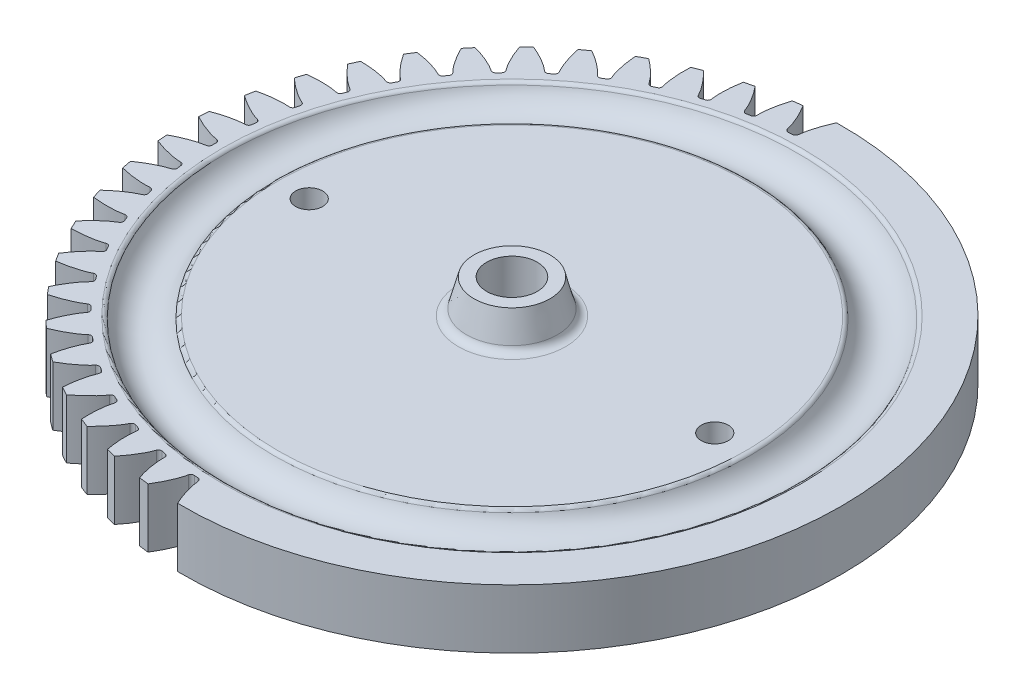
SolidWorks part; units mm, degrees
ref_plane "前视基准面" through (0, 0, 0) normal (0, 0, 1) x (1, 0, 0)
ref_plane "上视基准面" through (0, 0, 0) normal (0, 1, 0) x (1, 0, 0)
ref_plane "右视基准面" through (0, 0, 0) normal (1, 0, 0) x (0, 0, -1)
ref_plane "基准面1" through (0, 0, 0) normal (0, 0, -1) x (-1, 0, 0)
sketch "草图1" plane through (0, 0, 0) normal (0, 0, -1) x (-1, 0, 0)
  line L0 (-39, -7) -> (0, -7)
  line L1 (0, -7) -> (0, 0)
  line L2 (0, 0) -> (-28.0129, 0)
  line L3 (-33.9871, 0) -> (-39, 0)
  line L4 (-39, 0) -> (-39, -7)
  line L5 (0, -7) -> (0, 0) construction
  arc A0 (-28.0129, 0) -> (-33.9871, 0) centre (-31, 1) cw
  dimension "D1" = 3.15
  dimension "D2" = 5.0129
  dimension "D3" = 8
  dimension "D4" = 7
  dimension "D5" = 39
revolve "旋转1" add sketch "草图1" angle 360 about L5
sketch "草图2" plane through (0, -7, 0) normal (0, -1, 0) x (1, 0, 0)
  arc A0 (-1.6317, -35.2007) -> (-2.793, -35.1276) centre (0, 0) cw
  arc A1 (-4.3126, -38.7608) -> (-0.5795, -38.9957) centre (0, 0) ccw
  circle A2 centre (0, 0) radius 39 construction
  ellipse E0 centre (0.3268, -38.0783) end of major axis (1.9435, -41.9121) minor radius 1.2 (-1.6317, -35.2007) -> (-0.5795, -38.9957) ccw
  ellipse E1 centre (-5.0967, -37.737) end of major axis (-7.1811, -41.338) minor radius 1.2 (-4.3126, -38.7608) -> (-2.793, -35.1276) ccw
  point P0 (0.3268, -38.0783)
  point P1 (1.4326, -37.612)
  point P2 (1.9435, -41.9121)
  point P3 (-1.6317, -35.2007)
  point P4 (-0.5795, -38.9957)
  point P5 (-1.3943, -36.7453)
  point P6 (2.048, -39.4112)
  point P16 (-5.0967, -37.737)
  point P17 (-4.0582, -38.3382)
  point P18 (-3.0124, -34.136)
  point P19 (-4.3126, -38.7608)
  point P20 (-2.793, -35.1276)
  point P21 (-3.2221, -36.6303)
  point P22 (-6.9713, -38.8438)
  dimension "D1" = 35.2385
  dimension "D2" = 39
  dimension "D3" = 0.3268
  dimension "D4" = 1.4326
  dimension "D5" = 1.9435
  dimension "D6" = 2.048
  dimension "D7" = 0.5795
  dimension "D8" = 1.6317
  dimension "D9" = 2.793
  dimension "D10" = 1.3943
  dimension "D11" = 3.0124
  dimension "D12" = 4.0582
  dimension "D13" = 4.3126
  dimension "D14" = 3.2221
  dimension "D15" = 5.0967
  dimension "D16" = 34.136
  dimension "D17" = 34.2444
  dimension "D19" = 6.9713
  dimension "D21" = 36.6303
  dimension "D22" = 36.7453
  dimension "D30" = 38.8438
  dimension "D32" = 39.4112
extrude "切除-拉伸1" cut sketch "草图2" against normal through all
sketch "草图3" plane through (0, -7, 0) normal (0, -1, 0) x (1, 0, 0)
  arc A0 (-6.0306, -34.7186) -> (-7.1736, -34.5006) centre (0, 0) cw
  arc A1 (-9.1366, -37.9147) -> (-5.4623, -38.6156) centre (0, 0) ccw
  ellipse E0 centre (-4.4482, -37.819) end of major axis (-3.3248, -41.8252) minor radius 1.2 (-6.0306, -34.7186) -> (-5.4623, -38.6156) ccw
  ellipse E1 centre (-9.7863, -36.8007) end of major axis (-12.3055, -40.112) minor radius 1.2 (-9.1366, -37.9147) -> (-7.1736, -34.5006) ccw
  point P0 (-4.4482, -37.819)
  point P1 (-3.2927, -37.495)
  point P2 (-3.3248, -41.8252)
  point P3 (-6.0306, -34.7186)
  point P4 (-5.4623, -38.6156)
  point P5 (-5.9887, -36.2808)
  point P6 (-2.9077, -39.3571)
  point P16 (-9.7863, -36.8007)
  point P17 (-8.8312, -37.5273)
  point P18 (-7.267, -33.4893)
  point P19 (-9.1366, -37.9147)
  point P20 (-7.1736, -34.5006)
  point P21 (-7.7877, -35.9376)
  point P22 (-11.7848, -37.6637)
  dimension "D1" = 35.2385
  dimension "D2" = 39
  dimension "D3" = 0.5795
  dimension "D4" = 2.3283
  dimension "D5" = 2.7133
  dimension "D6" = 2.7454
  dimension "D7" = 3.8687
  dimension "D8" = 4.8829
  dimension "D9" = 5.4512
  dimension "D10" = 6.5942
  dimension "D11" = 5.4092
  dimension "D12" = 6.6875
  dimension "D13" = 8.2517
  dimension "D14" = 8.5571
  dimension "D15" = 7.2083
  dimension "D16" = 9.2068
  dimension "D17" = 0.3801
  dimension "D20" = 11.2053
  dimension "D22" = 1.332
  dimension "D26" = 2.7149
  dimension "D28" = 3.0581
  dimension "D34" = 0.3614
extrude "切除-拉伸2" cut sketch "草图3" against normal through all
sketch "草图4" plane through (0, -7, 0) normal (0, -1, 0) x (1, 0, 0)
  arc A0 (-10.3345, -33.689) -> (-11.4411, -33.3294) centre (0, 0) cw
  arc A1 (-13.8165, -36.4706) -> (-10.2591, -37.6265) centre (0, 0) ccw
  ellipse E0 centre (-9.1531, -36.9632) end of major axis (-8.5407, -41.0787) minor radius 1.2 (-10.3345, -33.689) -> (-10.2591, -37.6265) ccw
  ellipse E1 centre (-14.3214, -35.2839) end of major axis (-11.407, -32.3144) minor radius 1.2 (-13.8165, -36.4706) -> (-11.4411, -33.3294) ccw
  point P0 (-9.1531, -36.9632)
  point P1 (-7.9661, -36.7866)
  point P2 (-8.5407, -41.0787)
  point P3 (-10.3345, -33.689)
  point P4 (-10.2591, -37.6265)
  point P5 (-10.4886, -35.2441)
  point P6 (-7.8175, -38.6823)
  point P16 (-14.3214, -35.2839)
  point P17 (-13.465, -36.1245)
  point P18 (-11.407, -32.3144)
  point P19 (-13.8165, -36.4706)
  point P20 (-11.4411, -33.3294)
  point P21 (-12.2305, -34.6782)
  point P22 (-16.4124, -35.8897)
  dimension "D1" = 35.2385
  dimension "D2" = 39
  dimension "D3" = 1.6317
  dimension "D4" = 6.1859
  dimension "D5" = 6.3345
  dimension "D6" = 6.909
  dimension "D7" = 7.5214
  dimension "D8" = 8.6274
  dimension "D9" = 8.7028
  dimension "D10" = 9.7753
  dimension "D11" = 9.8095
  dimension "D12" = 8.857
  dimension "D13" = 11.8333
  dimension "D14" = 12.1848
  dimension "D15" = 10.5988
  dimension "D16" = 12.6898
  dimension "D17" = 0.0785
  dimension "D18" = 0.5074
  dimension "D20" = 14.7807
  dimension "D26" = 2.8711
  dimension "D28" = 3.5167
  dimension "D29" = 4.0826
extrude "切除-拉伸3" cut sketch "草图4" against normal through all
sketch "草图5" plane through (0, -7, 0) normal (0, -1, 0) x (1, 0, 0)
  arc A0 (-14.4753, -32.1281) -> (-15.5282, -31.6327) centre (0, 0) cw
  arc A1 (-18.2785, -34.4513) -> (-14.894, -36.044) centre (0, 0) ccw
  ellipse E0 centre (-13.7136, -35.5246) end of major axis (-13.6219, -39.6843) minor radius 1.2 (-14.4753, -32.1281) -> (-14.894, -36.044) ccw
  ellipse E1 centre (-18.6308, -33.2108) end of major axis (-21.8944, -35.7916) minor radius 1.2 (-18.2785, -34.4513) -> (-15.5282, -31.6327) ccw
  point P0 (-13.7136, -35.5246)
  point P1 (-12.5139, -35.4981)
  point P2 (-13.6219, -39.6843)
  point P3 (-14.4753, -32.1281)
  point P4 (-14.894, -36.044)
  point P5 (-14.8232, -33.6517)
  point P6 (-12.6041, -37.3975)
  point P16 (-18.6308, -33.2108)
  point P17 (-15.3671, -30.63)
  point P18 (-19.3751, -32.2695)
  point P19 (-18.2785, -34.4513)
  point P20 (-15.5282, -31.6327)
  point P21 (-16.4804, -32.8719)
  point P22 (-20.7811, -33.5497)
  dimension "D1" = 35.2385
  dimension "D2" = 39
  dimension "D3" = 4.3126
  dimension "D4" = 8.2013
  dimension "D5" = 8.2915
  dimension "D6" = 9.3093
  dimension "D7" = 9.4011
  dimension "D8" = 10.1628
  dimension "D9" = 10.5815
  dimension "D10" = 10.5106
  dimension "D11" = 11.0546
  dimension "D12" = 11.2156
  dimension "D13" = 13.5738
  dimension "D14" = 13.966
  dimension "D15" = 12.1678
  dimension "D16" = 14.3182
  dimension "D17" = 1.3633
  dimension "D18" = 2.7169
  dimension "D20" = 16.4686
  dimension "D26" = 5.1092
  dimension "D27" = 5.2111
  dimension "D29" = 5.889
extrude "切除-拉伸4" cut sketch "草图5" against normal through all
sketch "草图6" plane through (0, -7, 0) normal (0, -1, 0) x (1, 0, 0)
  arc A0 (-18.3879, -30.0605) -> (-19.3704, -29.437) centre (0, 0) cw
  arc A1 (-22.4523, -31.8888) -> (-19.2941, -33.893) centre (0, 0) ccw
  ellipse E0 centre (-18.0579, -33.5257) end of major axis (-18.4882, -37.6641) minor radius 1.2 (-18.3879, -30.0605) -> (-19.2941, -33.893) ccw
  ellipse E1 centre (-22.6463, -30.6138) end of major axis (-19.0849, -28.4624) minor radius 1.2 (-22.4523, -31.8888) -> (-19.3704, -29.437) ccw
  point P0 (-18.0579, -33.5257)
  point P1 (-16.8643, -33.6498)
  point P2 (-18.4882, -37.6641)
  point P3 (-18.3879, -30.0605)
  point P4 (-19.2941, -33.893)
  point P5 (-18.924, -31.5285)
  point P6 (-17.1918, -35.5229)
  point P16 (-22.6463, -30.6138)
  point P17 (-19.0849, -28.4624)
  point P18 (-23.2668, -29.5867)
  point P19 (-22.4523, -31.8888)
  point P20 (-19.3704, -29.437)
  point P21 (-20.4704, -30.5471)
  point P22 (-24.8222, -30.6806)
  dimension "D1" = 35.2385
  dimension "D2" = 39
  dimension "D3" = 6.0306
  dimension "D4" = 10.8337
  dimension "D5" = 11.1612
  dimension "D6" = 11.597
  dimension "D7" = 12.0273
  dimension "D8" = 12.3573
  dimension "D9" = 13.0543
  dimension "D10" = 12.8934
  dimension "D11" = 13.2635
  dimension "D12" = 13.3398
  dimension "D13" = 15.9951
  dimension "D14" = 16.4217
  dimension "D15" = 14.4397
  dimension "D16" = 16.6156
  dimension "D17" = 0.6075
  dimension "D20" = 18.7915
  dimension "D25" = 2.9721
  dimension "D26" = 3.82
  dimension "D28" = 3.9535
  dimension "D35" = 1.0223
extrude "切除-拉伸5" cut sketch "草图6" against normal through all
sketch "草图7" plane through (0, -7, 0) normal (0, -1, 0) x (1, 0, 0)
  arc A0 (-22.0105, -27.5189) -> (-22.9071, -26.7771) centre (0, 0) cw
  arc A1 (-26.272, -28.8233) -> (-23.3899, -31.2076) centre (0, 0) ccw
  ellipse E0 centre (-22.1174, -30.9981) end of major axis (-21.1718, -26.9462) minor radius 1.2 (-22.0105, -27.5189) -> (-23.3899, -31.2076) ccw
  ellipse E1 centre (-26.3046, -27.5341) end of major axis (-30.1075, -29.2222) minor radius 1.2 (-26.272, -28.8233) -> (-22.9071, -26.7771) ccw
  point P0 (-22.1174, -30.9981)
  point P1 (-20.9488, -31.2708)
  point P2 (-23.063, -35.0499)
  point P3 (-22.0105, -27.5189)
  point P4 (-23.3899, -31.2076)
  point P5 (-22.7263, -28.908)
  point P6 (-21.5085, -33.0881)
  point P16 (-26.3046, -27.5341)
  point P17 (-22.5017, -25.846)
  point P18 (-26.7915, -26.4373)
  point P19 (-26.272, -28.8233)
  point P20 (-22.9071, -26.7771)
  point P21 (-24.1375, -27.7406)
  point P22 (-28.4717, -27.3276)
  dimension "D1" = 35.2385
  dimension "D2" = 39
  dimension "D3" = 9.1366
  dimension "D4" = 11.8122
  dimension "D5" = 12.0352
  dimension "D6" = 12.3719
  dimension "D7" = 12.8739
  dimension "D8" = 12.9808
  dimension "D9" = 13.3651
  dimension "D10" = 13.5898
  dimension "D11" = 13.7705
  dimension "D12" = 14.2533
  dimension "D13" = 16.6812
  dimension "D14" = 17.1354
  dimension "D15" = 15.0009
  dimension "D16" = 17.168
  dimension "D17" = 2.8647
  dimension "D18" = 4.8266
  dimension "D20" = 19.3351
  dimension "D25" = 9.0066
  dimension "D28" = 10.1741
  dimension "D31" = 10.5871
extrude "切除-拉伸6" cut sketch "草图7" against normal through all
sketch "草图8" plane through (0, -7, 0) normal (0, -1, 0) x (1, 0, 0)
  arc A0 (-25.286, -24.5432) -> (-26.0825, -23.695) centre (0, 0) cw
  arc A1 (-29.6773, -25.3033) -> (-27.1168, -28.03) centre (0, 0) ccw
  ellipse E0 centre (-25.8281, -27.9816) end of major axis (-27.2741, -31.883) minor radius 1.2 (-25.286, -24.5432) -> (-27.1168, -28.03) ccw
  ellipse E1 centre (-29.5481, -24.0202) end of major axis (-25.5636, -22.822) minor radius 1.2 (-29.6773, -25.3033) -> (-26.0825, -23.695) ccw
  point P0 (-25.8281, -27.9816)
  point P1 (-24.7029, -28.3986)
  point P2 (-27.2741, -31.883)
  point P3 (-25.286, -24.5432)
  point P4 (-27.1168, -28.03)
  point P5 (-26.1703, -25.8317)
  point P6 (-25.4859, -30.1315)
  point P16 (-29.5481, -24.0202)
  point P17 (-25.5636, -22.822)
  point P18 (-29.8937, -22.871)
  point P19 (-29.6773, -25.3033)
  point P20 (-26.0825, -23.695)
  point P21 (-27.424, -24.4966)
  point P22 (-31.6723, -23.5437)
  dimension "D1" = 35.2385
  dimension "D2" = 39
  dimension "D3" = 10.3345
  dimension "D4" = 14.0477
  dimension "D5" = 14.3684
  dimension "D6" = 14.9515
  dimension "D7" = 15.1515
  dimension "D8" = 15.2292
  dimension "D9" = 15.4936
  dimension "D10" = 15.7481
  dimension "D11" = 15.8358
  dimension "D12" = 16.7823
  dimension "D13" = 18.8681
  dimension "D14" = 19.2137
  dimension "D15" = 17.0895
  dimension "D16" = 19.3429
  dimension "D17" = 1.4464
  dimension "D18" = 3.198
  dimension "D20" = 21.3378
  dimension "D24" = 7.4977
  dimension "D29" = 8.8328
  dimension "D33" = 9.7858
extrude "切除-拉伸7" cut sketch "草图8" against normal through all
sketch "草图9" plane through (0, -7, 0) normal (0, -1, 0) x (1, 0, 0)
  arc A0 (-28.1627, -21.1805) -> (-28.8466, -20.2391) centre (0, 0) cw
  arc A1 (-32.6147, -21.3842) -> (-30.4161, -24.4103) centre (0, 0) ccw
  ellipse E0 centre (-29.1315, -24.5238) end of major axis (-27.2079, -20.8344) minor radius 1.2 (-28.1627, -21.1805) -> (-30.4161, -24.4103) ccw
  ellipse E1 centre (-32.3257, -20.1274) end of major axis (-28.2224, -19.4381) minor radius 1.2 (-32.6147, -21.3842) -> (-28.8466, -20.2391) ccw
  point P0 (-29.1315, -24.5238)
  point P1 (-28.0674, -25.0786)
  point P2 (-31.055, -28.2132)
  point P3 (-28.1627, -21.1805)
  point P4 (-30.4161, -24.4103)
  point P5 (-29.2015, -22.348)
  point P6 (-29.0614, -26.6996)
  point P16 (-32.3257, -20.1274)
  point P17 (-28.2224, -19.4381)
  point P18 (-32.5245, -18.9439)
  point P19 (-32.6147, -21.3842)
  point P20 (-28.8466, -20.2391)
  point P21 (-30.278, -20.8663)
  point P22 (-34.3733, -19.3884)
  dimension "D1" = 35.2385
  dimension "D2" = 39
  dimension "D3" = 13.8165
  dimension "D4" = 13.3914
  dimension "D5" = 14.2509
  dimension "D6" = 14.3462
  dimension "D7" = 14.4059
  dimension "D8" = 15.0301
  dimension "D9" = 15.2449
  dimension "D10" = 15.315
  dimension "D11" = 15.385
  dimension "D12" = 16.5996
  dimension "D13" = 16.4615
  dimension "D14" = 18.3104
  dimension "D15" = 18.5092
  dimension "D16" = 18.7982
  dimension "D17" = 8.2573
  dimension "D18" = 9.771
  dimension "D20" = 20.5568
  dimension "D24" = 14.1226
  dimension "D28" = 15.6043
  dimension "D34" = 17.0822
extrude "切除-拉伸8" cut sketch "草图9" against normal through all
sketch "草图10" plane through (0, -7, 0) normal (0, -1, 0) x (1, 0, 0)
  arc A0 (-30.5952, -17.4838) -> (-31.1558, -16.4641) centre (0, 0) cw
  arc A1 (-35.0376, -17.1279) -> (-33.2356, -20.4057) centre (0, 0) ccw
  ellipse E0 centre (-31.9754, -20.6793) end of major axis (-34.3462, -24.0986) minor radius 1.2 (-30.5952, -17.4838) -> (-33.2356, -20.4057) ccw
  ellipse E1 centre (-34.5934, -15.9172) end of major axis (-30.4361, -15.7476) minor radius 1.2 (-35.0376, -17.1279) -> (-31.1558, -16.4641) ccw
  point P0 (-31.9754, -20.6793)
  point P1 (-30.9892, -21.3631)
  point P2 (-34.3462, -24.0986)
  point P3 (-30.5952, -17.4838)
  point P4 (-33.2356, -20.4057)
  point P5 (-31.7722, -18.5119)
  point P6 (-32.1786, -22.8467)
  point P16 (-34.5934, -15.9172)
  point P17 (-30.4361, -15.7476)
  point P18 (-34.6423, -14.7182)
  point P19 (-35.0376, -17.1279)
  point P20 (-31.1558, -16.4641)
  point P21 (-32.6545, -16.907)
  point P22 (-36.5323, -14.9274)
  dimension "D1" = 35.2385
  dimension "D2" = 39
  dimension "D3" = 14.4753
  dimension "D4" = 15.1293
  dimension "D5" = 15.9608
  dimension "D6" = 16.1199
  dimension "D7" = 16.5139
  dimension "D8" = 16.6805
  dimension "D9" = 17.2968
  dimension "D10" = 17.5001
  dimension "D11" = 17.7033
  dimension "D12" = 18.1792
  dimension "D13" = 18.7603
  dimension "D14" = 20.0692
  dimension "D15" = 20.1181
  dimension "D16" = 20.5623
  dimension "D17" = 7.5341
  dimension "D18" = 8.7859
  dimension "D20" = 22.057
  dimension "D24" = 13.1207
  dimension "D29" = 14.7257
  dimension "D34" = 16.7052
extrude "切除-拉伸9" cut sketch "草图10" against normal through all
sketch "草图11" plane through (0, -7, 0) normal (0, -1, 0) x (1, 0, 0)
  arc A0 (-32.5453, -13.5113) -> (-32.9736, -12.4294) centre (0, 0) cw
  arc A1 (-36.908, -12.6014) -> (-35.5311, -16.0792) centre (0, 0) ccw
  ellipse E0 centre (-34.3151, -16.5087) end of major axis (-37.0957, -19.6038) minor radius 1.2 (-32.5453, -13.5113) -> (-35.5311, -16.0792) ccw
  ellipse E1 centre (-36.3156, -11.456) end of major axis (-32.1698, -11.8088) minor radius 1.2 (-36.908, -12.6014) -> (-32.9736, -12.4294) ccw
  point P0 (-34.3151, -16.5087)
  point P1 (-33.4224, -17.3107)
  point P2 (-37.0957, -19.6038)
  point P3 (-32.5453, -13.5113)
  point P4 (-35.5311, -16.0792)
  point P5 (-33.8418, -14.3838)
  point P6 (-34.7883, -18.6335)
  point P16 (-36.3156, -11.456)
  point P17 (-32.1698, -11.8088)
  point P18 (-36.2138, -10.2603)
  point P19 (-36.908, -12.6014)
  point P20 (-32.9736, -12.4294)
  point P21 (-34.516, -12.6809)
  point P22 (-38.1151, -10.231)
  dimension "D1" = 35.2385
  dimension "D2" = 39
  dimension "D3" = 18.2785
  dimension "D4" = 13.2559
  dimension "D5" = 13.8913
  dimension "D6" = 14.2667
  dimension "D7" = 14.6951
  dimension "D8" = 15.1438
  dimension "D9" = 15.5633
  dimension "D10" = 16.0365
  dimension "D11" = 16.2375
  dimension "D12" = 16.5098
  dimension "D13" = 17.2525
  dimension "D14" = 17.9353
  dimension "D15" = 18.037
  dimension "D16" = 18.6295
  dimension "D17" = 14.8475
  dimension "D18" = 15.8178
  dimension "D20" = 19.8366
  dimension "D24" = 20.0675
  dimension "D27" = 21.7704
  dimension "D35" = 24.2203
extrude "切除-拉伸10" cut sketch "草图11" against normal through all
sketch "草图12" plane through (0, -7, 0) normal (0, -1, 0) x (1, 0, 0)
  arc A0 (-33.982, -9.3258) -> (-34.2714, -8.1987) centre (0, 0) cw
  arc A1 (-38.1964, -7.8763) -> (-37.2662, -11.4992) centre (0, 0) ccw
  ellipse E0 centre (-36.1136, -12.0777) end of major axis (-32.9669, -9.3555) minor radius 1.2 (-33.982, -9.3258) -> (-37.2662, -11.4992) ccw
  ellipse E1 centre (-37.465, -6.8141) end of major axis (-33.3962, -7.6837) minor radius 1.2 (-38.1964, -7.8763) -> (-34.2714, -8.1987) ccw
  point P0 (-36.1136, -12.0777)
  point P1 (-32.9669, -9.3555)
  point P2 (-35.3284, -12.9852)
  point P3 (-33.982, -9.3258)
  point P4 (-37.2662, -11.4992)
  point P5 (-35.3777, -10.0289)
  point P6 (-36.8494, -14.1265)
  point P16 (-37.465, -6.8141)
  point P17 (-33.3962, -7.6837)
  point P18 (-37.2142, -5.6406)
  point P19 (-38.1964, -7.8763)
  point P20 (-34.2714, -8.1987)
  point P21 (-35.8332, -8.255)
  point P22 (-39.0969, -5.3732)
  dimension "D1" = 35.2385
  dimension "D2" = 39
  dimension "D3" = 18.3879
  dimension "D4" = 14.579
  dimension "D5" = 15.0083
  dimension "D6" = 15.5941
  dimension "D7" = 15.8835
  dimension "D8" = 16.9405
  dimension "D9" = 16.9898
  dimension "D10" = 17.4453
  dimension "D11" = 17.7257
  dimension "D12" = 18.4615
  dimension "D13" = 18.8263
  dimension "D14" = 18.8783
  dimension "D15" = 19.0771
  dimension "D16" = 19.8085
  dimension "D17" = 14.6371
  dimension "D18" = 15.3106
  dimension "D19" = 20.709
  dimension "D24" = 19.4081
  dimension "D27" = 21.1821
  dimension "D35" = 24.0638
extrude "切除-拉伸11" cut sketch "草图12" against normal through all
sketch "草图13" plane through (0, -7, 0) normal (0, -1, 0) x (1, 0, 0)
  arc A0 (-34.8829, -4.9932) -> (-35.0288, -3.8387) centre (0, 0) cw
  arc A1 (-38.8824, -3.0269) -> (-38.4136, -6.7379) centre (0, 0) ccw
  ellipse E0 centre (-37.3425, -7.4562) end of major axis (-40.8055, -9.7626) minor radius 1.2 (-34.8829, -4.9932) -> (-38.4136, -6.7379) ccw
  ellipse E1 centre (-38.0236, -2.0647) end of major axis (-34.0959, -3.4375) minor radius 1.2 (-38.8824, -3.0269) -> (-35.0288, -3.8387) ccw
  point P0 (-37.3425, -7.4562)
  point P1 (-33.8795, -5.1498)
  point P2 (-36.6773, -8.455)
  point P3 (-34.8829, -4.9932)
  point P4 (-38.4136, -6.7379)
  point P5 (-36.3557, -5.5158)
  point P6 (-38.3294, -9.3966)
  point P16 (-38.0236, -2.0647)
  point P17 (-34.0959, -3.4375)
  point P18 (-37.6277, -0.9319)
  point P19 (-38.8824, -3.0269)
  point P20 (-35.0288, -3.8387)
  point P21 (-36.5853, -3.6988)
  point P22 (-39.462, -0.4307)
  dimension "D1" = 35.2385
  dimension "D2" = 39
  dimension "D3" = 22.0105
  dimension "D4" = 11.869
  dimension "D5" = 12.0854
  dimension "D6" = 12.8724
  dimension "D7" = 13.0183
  dimension "D8" = 14.3452
  dimension "D9" = 14.5748
  dimension "D10" = 14.6668
  dimension "D11" = 15.332
  dimension "D12" = 15.6172
  dimension "D13" = 16.0131
  dimension "D14" = 16.4031
  dimension "D15" = 16.3189
  dimension "D16" = 16.8719
  dimension "D17" = 22.1262
  dimension "D18" = 22.4922
  dimension "D19" = 17.4515
  dimension "D24" = 26.373
  dimension "D28" = 28.19
  dimension "D35" = 31.458
extrude "切除-拉伸12" cut sketch "草图13" against normal through all
sketch "草图14" plane through (0, -7, 0) normal (0, -1, 0) x (1, 0, 0)
  arc A0 (-35.2337, -0.5818) -> (-35.2337, 0.5818) centre (0, 0) cw
  arc A1 (-38.9551, 1.8702) -> (-38.9551, -1.8702) centre (0, 0) ccw
  ellipse E0 centre (-37.9826, -2.7172) end of major axis (-34.2578, -0.863) minor radius 1.2 (-35.2337, -0.5818) -> (-38.9551, -1.8702) ccw
  ellipse E1 centre (-37.9826, 2.7172) end of major axis (-34.2578, 0.863) minor radius 1.2 (-38.9551, 1.8702) -> (-35.2337, 0.5818) ccw
  point P0 (-37.9826, -2.7172)
  point P1 (-34.2578, -0.863)
  point P2 (-37.4478, -3.7914)
  point P3 (-35.2337, -0.5818)
  point P4 (-38.9551, -1.8702)
  point P5 (-36.7603, -0.9157)
  point P6 (-39.2048, -4.5186)
  point P16 (-37.9826, 2.7172)
  point P17 (-34.2578, 0.863)
  point P18 (-37.4478, 3.7914)
  point P19 (-38.9551, 1.8702)
  point P20 (-35.2337, 0.5818)
  point P21 (-36.7603, 0.9157)
  point P22 (-39.2048, 4.5186)
  dimension "D1" = 35.2385
  dimension "D2" = 39
  dimension "D3" = 22.0105
  dimension "D4" = 12.2473
  dimension "D5" = 13.2232
  dimension "D6" = 14.7499
  dimension "D7" = 15.4373
  dimension "D8" = 16.5069
  dimension "D9" = 16.9446
  dimension "D10" = 22.2058
  dimension "D11" = 17.1943
  dimension "D12" = 22.2586
  dimension "D17" = 25.8614
  dimension "D23" = 27.6929
  dimension "D28" = 31.2957
extrude "切除-拉伸13" cut sketch "草图14" against normal through all
sketch "草图15" plane through (0, -7, 0) normal (0, -1, 0) x (1, 0, 0)
  arc A0 (-35.0288, 3.8387) -> (-34.8829, 4.9932) centre (0, 0) cw
  arc A1 (-38.4136, 6.7379) -> (-38.8824, 3.0269) centre (0, 0) ccw
  ellipse E0 centre (-38.0236, 2.0647) end of major axis (-34.0959, 3.4375) minor radius 1.2 (-35.0288, 3.8387) -> (-38.8824, 3.0269) ccw
  ellipse E1 centre (-37.3425, 7.4562) end of major axis (-33.8795, 5.1498) minor radius 1.2 (-38.4136, 6.7379) -> (-34.8829, 4.9932) ccw
  point P0 (-38.0236, 2.0647)
  point P1 (-34.0959, 3.4375)
  point P2 (-37.6277, 0.9319)
  point P3 (-35.0288, 3.8387)
  point P4 (-38.8824, 3.0269)
  point P5 (-36.5853, 3.6988)
  point P6 (-39.462, 0.4307)
  point P16 (-37.3425, 7.4562)
  point P17 (-33.8795, 5.1498)
  point P18 (-36.6773, 8.455)
  point P19 (-38.4136, 6.7379)
  point P20 (-34.8829, 4.9932)
  point P21 (-36.3557, 5.5158)
  point P22 (-38.3294, 9.3966)
  dimension "D1" = 35.2385
  dimension "D2" = 39
  dimension "D3" = 25.286
  dimension "D4" = 8.5936
  dimension "D5" = 8.8099
  dimension "D6" = 9.597
  dimension "D7" = 9.7428
  dimension "D8" = 11.0697
  dimension "D9" = 11.2993
  dimension "D10" = 11.3914
  dimension "D11" = 12.0566
  dimension "D12" = 12.3418
  dimension "D13" = 12.7377
  dimension "D14" = 13.1276
  dimension "D15" = 13.0434
  dimension "D16" = 13.5964
  dimension "D17" = 28.8233
  dimension "D18" = 29.254
  dimension "D19" = 14.1761
  dimension "D26" = 32.5221
  dimension "D30" = 34.3391
  dimension "D35" = 38.2199
extrude "切除-拉伸14" cut sketch "草图15" against normal through all
sketch "草图16" plane through (0, -7, 0) normal (0, -1, 0) x (1, 0, 0)
  arc A0 (-34.2714, 8.1987) -> (-33.982, 9.3258) centre (0, 0) cw
  arc A1 (-37.2662, 11.4992) -> (-38.1964, 7.8763) centre (0, 0) ccw
  ellipse E0 centre (-37.465, 6.8141) end of major axis (-41.5339, 5.9445) minor radius 1.2 (-34.2714, 8.1987) -> (-38.1964, 7.8763) ccw
  ellipse E1 centre (-36.1136, 12.0777) end of major axis (-32.9669, 9.3555) minor radius 1.2 (-37.2662, 11.4992) -> (-33.982, 9.3258) ccw
  point P0 (-37.465, 6.8141)
  point P1 (-33.3962, 7.6837)
  point P2 (-37.2142, 5.6406)
  point P3 (-34.2714, 8.1987)
  point P4 (-38.1964, 7.8763)
  point P5 (-35.8332, 8.255)
  point P6 (-39.0969, 5.3732)
  point P16 (-36.1136, 12.0777)
  point P17 (-32.9669, 9.3555)
  point P18 (-35.3284, 12.9852)
  point P19 (-37.2662, 11.4992)
  point P20 (-33.982, 9.3258)
  point P21 (-35.3777, 10.0289)
  point P22 (-36.8494, 14.1265)
  dimension "D1" = 35.2385
  dimension "D2" = 39
  dimension "D3" = 25.286
  dimension "D4" = 7.681
  dimension "D5" = 8.1102
  dimension "D6" = 8.6961
  dimension "D7" = 8.9855
  dimension "D8" = 10.0425
  dimension "D9" = 10.0918
  dimension "D10" = 10.5472
  dimension "D11" = 10.8276
  dimension "D12" = 11.5635
  dimension "D13" = 11.9283
  dimension "D14" = 11.9802
  dimension "D15" = 12.1791
  dimension "D16" = 12.9104
  dimension "D17" = 23.695
  dimension "D18" = 29.0682
  dimension "D19" = 13.8109
  dimension "D27" = 31.9499
  dimension "D30" = 33.7239
  dimension "D35" = 37.8214
extrude "切除-拉伸15" cut sketch "草图16" against normal through all
sketch "草图17" plane through (0, -7, 0) normal (0, -1, 0) x (1, 0, 0)
  arc A0 (-32.9736, 12.4294) -> (-32.5453, 13.5113) centre (0, 0) cw
  arc A1 (-35.5311, 16.0792) -> (-36.908, 12.6014) centre (0, 0) ccw
  ellipse E0 centre (-36.3156, 11.456) end of major axis (-32.1698, 11.8088) minor radius 1.2 (-32.9736, 12.4294) -> (-36.908, 12.6014) ccw
  ellipse E1 centre (-34.3151, 16.5087) end of major axis (-31.5344, 13.4135) minor radius 1.2 (-35.5311, 16.0792) -> (-32.5453, 13.5113) ccw
  point P0 (-36.3156, 11.456)
  point P1 (-32.1698, 11.8088)
  point P2 (-36.2138, 10.2603)
  point P3 (-32.9736, 12.4294)
  point P4 (-36.908, 12.6014)
  point P5 (-34.516, 12.6809)
  point P6 (-38.1151, 10.231)
  point P16 (-34.3151, 16.5087)
  point P17 (-33.4224, 17.3107)
  point P18 (-37.0957, 19.6038)
  point P19 (-35.5311, 16.0792)
  point P20 (-32.5453, 13.5113)
  point P21 (-33.8418, 14.3838)
  point P22 (-34.7883, 18.6335)
  dimension "D1" = 35.2385
  dimension "D2" = 39
  dimension "D3" = 28.1627
  dimension "D4" = 3.3718
  dimension "D5" = 4.0072
  dimension "D6" = 4.3826
  dimension "D7" = 4.811
  dimension "D8" = 5.2597
  dimension "D9" = 5.6791
  dimension "D10" = 6.1524
  dimension "D11" = 6.3534
  dimension "D12" = 6.6257
  dimension "D13" = 7.3684
  dimension "D14" = 8.0512
  dimension "D15" = 8.1529
  dimension "D16" = 8.7454
  dimension "D17" = 25.3033
  dimension "D18" = 35.5343
  dimension "D20" = 9.9525
  dimension "D27" = 37.9842
  dimension "D30" = 39.6871
  dimension "D35" = 43.9368
extrude "切除-拉伸16" cut sketch "草图17" against normal through all
sketch "草图18" plane through (0, -7, 0) normal (0, -1, 0) x (1, 0, 0)
  arc A0 (-31.1558, 16.4641) -> (-30.5952, 17.4838) centre (0, 0) cw
  arc A1 (-33.2356, 20.4057) -> (-35.0376, 17.1279) centre (0, 0) ccw
  ellipse E0 centre (-34.5934, 15.9172) end of major axis (-30.4361, 15.7476) minor radius 1.2 (-31.1558, 16.4641) -> (-35.0376, 17.1279) ccw
  ellipse E1 centre (-31.9754, 20.6793) end of major axis (-29.6046, 17.2601) minor radius 1.2 (-33.2356, 20.4057) -> (-30.5952, 17.4838) ccw
  point P0 (-34.5934, 15.9172)
  point P1 (-30.4361, 15.7476)
  point P2 (-34.6423, 14.7182)
  point P3 (-31.1558, 16.4641)
  point P4 (-35.0376, 17.1279)
  point P5 (-32.6545, 16.907)
  point P6 (-36.5323, 14.9274)
  point P16 (-31.9754, 20.6793)
  point P17 (-30.9892, 21.3631)
  point P18 (-34.3462, 24.0986)
  point P19 (-33.2356, 20.4057)
  point P20 (-30.5952, 17.4838)
  point P21 (-31.7722, 18.5119)
  point P22 (-32.1786, 22.8467)
  dimension "D1" = 35.2385
  dimension "D2" = 39
  dimension "D3" = 28.1627
  dimension "D4" = 1.442
  dimension "D5" = 2.2735
  dimension "D6" = 2.4326
  dimension "D7" = 2.8266
  dimension "D8" = 2.9931
  dimension "D9" = 3.6095
  dimension "D10" = 3.8127
  dimension "D11" = 4.016
  dimension "D12" = 4.4918
  dimension "D13" = 5.073
  dimension "D14" = 6.3818
  dimension "D15" = 6.4307
  dimension "D16" = 6.875
  dimension "D17" = 20.2391
  dimension "D19" = 35.1666
  dimension "D20" = 8.3696
  dimension "D25" = 37.1461
  dimension "D30" = 38.751
  dimension "D35" = 43.0859
extrude "切除-拉伸17" cut sketch "草图18" against normal through all
sketch "草图19" plane through (0, -7, 0) normal (0, -1, 0) x (1, 0, 0)
  arc A0 (-28.8466, 20.2391) -> (-28.1627, 21.1805) centre (0, 0) cw
  arc A1 (-30.4161, 24.4103) -> (-32.6147, 21.3842) centre (0, 0) ccw
  ellipse E0 centre (-32.3257, 20.1274) end of major axis (-28.2224, 19.4381) minor radius 1.2 (-28.8466, 20.2391) -> (-32.6147, 21.3842) ccw
  ellipse E1 centre (-29.1315, 24.5238) end of major axis (-31.055, 28.2132) minor radius 1.2 (-30.4161, 24.4103) -> (-28.1627, 21.1805) ccw
  point P0 (-32.3257, 20.1274)
  point P1 (-28.2224, 19.4381)
  point P2 (-32.5245, 18.9439)
  point P3 (-28.8466, 20.2391)
  point P4 (-32.6147, 21.3842)
  point P5 (-30.278, 20.8663)
  point P6 (-34.3733, 19.3884)
  point P16 (-29.1315, 24.5238)
  point P17 (-28.0674, 25.0786)
  point P18 (-31.055, 28.2132)
  point P19 (-30.4161, 24.4103)
  point P20 (-28.1627, 21.1805)
  point P21 (-29.2015, 22.348)
  point P22 (-29.0614, 26.6996)
  dimension "D1" = 35.2385
  dimension "D2" = 39
  dimension "D3" = 0.1791
  dimension "D4" = 0.3172
  dimension "D5" = 0.3997
  dimension "D6" = 1.3937
  dimension "D7" = 1.4638
  dimension "D8" = 1.5338
  dimension "D9" = 1.7486
  dimension "D10" = 2.3728
  dimension "D11" = 2.4326
  dimension "D12" = 3.3873
  dimension "D13" = 30.5952
  dimension "D14" = 1.5316
  dimension "D15" = 1.7305
  dimension "D16" = 2.0195
  dimension "D17" = 21.3842
  dimension "D19" = 40.7726
  dimension "D20" = 3.7781
  dimension "D26" = 42.2505
  dimension "D30" = 43.7322
  dimension "D35" = 48.0838
extrude "切除-拉伸18" cut sketch "草图19" against normal through all
sketch "草图20" plane through (0, -7, 0) normal (0, -1, 0) x (1, 0, 0)
  arc A0 (-26.0825, 23.695) -> (-25.286, 24.5432) centre (0, 0) cw
  arc A1 (-27.1168, 28.03) -> (-29.6773, 25.3033) centre (0, 0) ccw
  ellipse E0 centre (-29.5481, 24.0202) end of major axis (-33.5326, 25.2183) minor radius 1.2 (-26.0825, 23.695) -> (-29.6773, 25.3033) ccw
  ellipse E1 centre (-25.8281, 27.9816) end of major axis (-27.2741, 31.883) minor radius 1.2 (-27.1168, 28.03) -> (-25.286, 24.5432) ccw
  point P0 (-29.5481, 24.0202)
  point P1 (-25.5636, 22.822)
  point P2 (-29.8937, 22.871)
  point P3 (-26.0825, 23.695)
  point P4 (-29.6773, 25.3033)
  point P5 (-27.424, 24.4966)
  point P6 (-31.6723, 23.5437)
  point P16 (-25.8281, 27.9816)
  point P17 (-24.7029, 28.3986)
  point P18 (-27.2741, 31.883)
  point P19 (-27.1168, 28.03)
  point P20 (-25.286, 24.5432)
  point P21 (-26.1703, 25.8317)
  point P22 (-25.4859, 30.1315)
  dimension "D1" = 35.2385
  dimension "D2" = 39
  dimension "D3" = 5.4225
  dimension "D4" = 7.2829
  dimension "D5" = 9.0614
  dimension "D6" = 9.2778
  dimension "D7" = 9.407
  dimension "D8" = 11.6811
  dimension "D9" = 11.5311
  dimension "D10" = 11.8383
  dimension "D11" = 12.0018
  dimension "D12" = 12.8726
  dimension "D13" = 12.7849
  dimension "D14" = 13.127
  dimension "D15" = 13.6692
  dimension "D16" = 38.9551
  dimension "D17" = 13.4692
  dimension "D18" = 16.4641
  dimension "D21" = 40.0078
  dimension "D25" = 40.9607
  dimension "D30" = 42.2958
  dimension "D35" = 46.5956
extrude "切除-拉伸19" cut sketch "草图20" against normal through all
sketch "草图21" plane through (0, -7, 0) normal (0, -1, 0) x (1, 0, 0)
  arc A0 (-22.9071, 26.7771) -> (-22.0105, 27.5189) centre (0, 0) cw
  arc A1 (-23.3899, 31.2076) -> (-26.272, 28.8233) centre (0, 0) ccw
  ellipse E0 centre (-26.3046, 27.5341) end of major axis (-30.1075, 29.2222) minor radius 1.2 (-22.9071, 26.7771) -> (-26.272, 28.8233) ccw
  ellipse E1 centre (-22.1174, 30.9981) end of major axis (-21.1718, 26.9462) minor radius 1.2 (-23.3899, 31.2076) -> (-22.0105, 27.5189) ccw
  point P0 (-26.3046, 27.5341)
  point P1 (-22.5017, 25.846)
  point P2 (-26.7915, 26.4373)
  point P3 (-22.9071, 26.7771)
  point P4 (-26.272, 28.8233)
  point P5 (-24.1375, 27.7406)
  point P6 (-28.4717, 27.3276)
  point P16 (-22.1174, 30.9981)
  point P17 (-20.9488, 31.2708)
  point P18 (-23.063, 35.0499)
  point P19 (-23.3899, 31.2076)
  point P20 (-22.0105, 27.5189)
  point P21 (-22.7263, 28.908)
  point P22 (-21.5085, 33.0881)
  dimension "D1" = 35.2385
  dimension "D2" = 39
  dimension "D3" = 8.8476
  dimension "D4" = 10.4834
  dimension "D5" = 12.1636
  dimension "D6" = 12.6505
  dimension "D7" = 12.6831
  dimension "D8" = 15.5652
  dimension "D9" = 14.8176
  dimension "D10" = 15.6691
  dimension "D11" = 15.8921
  dimension "D12" = 16.048
  dimension "D13" = 16.8377
  dimension "D14" = 16.2288
  dimension "D15" = 16.9446
  dimension "D16" = 38.9551
  dimension "D17" = 17.1279
  dimension "D18" = 17.4466
  dimension "D23" = 44.4555
  dimension "D26" = 44.8685
  dimension "D29" = 46.0359
  dimension "D35" = 50.216
extrude "切除-拉伸20" cut sketch "草图21" against normal through all
sketch "草图22" plane through (0, -7, 0) normal (0, -1, 0) x (1, 0, 0)
  arc A0 (-19.3704, 29.437) -> (-18.3879, 30.0605) centre (0, 0) cw
  arc A1 (-19.2941, 33.893) -> (-22.4523, 31.8888) centre (0, 0) ccw
  ellipse E0 centre (-22.6463, 30.6138) end of major axis (-19.0849, 28.4624) minor radius 1.2 (-19.3704, 29.437) -> (-22.4523, 31.8888) ccw
  ellipse E1 centre (-18.0579, 33.5257) end of major axis (-17.6276, 29.3873) minor radius 1.2 (-19.2941, 33.893) -> (-18.3879, 30.0605) ccw
  point P0 (-22.6463, 30.6138)
  point P1 (-19.0849, 28.4624)
  point P2 (-23.2668, 29.5867)
  point P3 (-19.3704, 29.437)
  point P4 (-22.4523, 31.8888)
  point P5 (-20.4704, 30.5471)
  point P6 (-24.8222, 30.6806)
  point P16 (-18.0579, 33.5257)
  point P17 (-16.8643, 33.6498)
  point P18 (-18.4882, 37.6641)
  point P19 (-19.2941, 33.893)
  point P20 (-18.3879, 30.0605)
  point P21 (-18.924, 31.5285)
  point P22 (-17.1918, 35.5229)
  dimension "D1" = 35.2385
  dimension "D2" = 39
  dimension "D3" = 12.7475
  dimension "D4" = 14.133
  dimension "D5" = 15.6884
  dimension "D6" = 16.3089
  dimension "D7" = 16.5028
  dimension "D8" = 19.5847
  dimension "D9" = 18.4848
  dimension "D10" = 19.661
  dimension "D11" = 19.7036
  dimension "D12" = 20.4669
  dimension "D13" = 20.5672
  dimension "D14" = 20.0311
  dimension "D15" = 20.8972
  dimension "D16" = 38.9551
  dimension "D17" = 12.4294
  dimension "D19" = 21.7633
  dimension "D24" = 42.9765
  dimension "D26" = 43.11
  dimension "D27" = 43.9579
  dimension "D35" = 47.9523
extrude "切除-拉伸21" cut sketch "草图22" against normal through all
sketch "草图23" plane through (0, -7, 0) normal (0, -1, 0) x (1, 0, 0)
  arc A0 (-15.5282, 31.6327) -> (-14.4753, 32.1281) centre (0, 0) cw
  arc A1 (-14.894, 36.044) -> (-18.2785, 34.4513) centre (0, 0) ccw
  ellipse E0 centre (-18.6308, 33.2108) end of major axis (-21.8944, 35.7916) minor radius 1.2 (-15.5282, 31.6327) -> (-18.2785, 34.4513) ccw
  ellipse E1 centre (-13.7136, 35.5246) end of major axis (-13.6219, 39.6843) minor radius 1.2 (-14.894, 36.044) -> (-14.4753, 32.1281) ccw
  point P0 (-18.6308, 33.2108)
  point P1 (-15.3671, 30.63)
  point P2 (-19.3751, 32.2695)
  point P3 (-15.5282, 31.6327)
  point P4 (-18.2785, 34.4513)
  point P5 (-16.4804, 32.8719)
  point P6 (-20.7811, 33.5497)
  point P16 (-13.7136, 35.5246)
  point P17 (-12.5139, 35.4981)
  point P18 (-13.6219, 39.6843)
  point P19 (-14.894, 36.044)
  point P20 (-14.4753, 32.1281)
  point P21 (-14.8232, 33.6517)
  point P22 (-12.6041, 37.3975)
  dimension "D1" = 35.2385
  dimension "D2" = 39
  dimension "D3" = 17.0607
  dimension "D4" = 18.174
  dimension "D5" = 19.58
  dimension "D6" = 20.3244
  dimension "D7" = 20.6766
  dimension "D8" = 23.4269
  dimension "D9" = 22.4747
  dimension "D10" = 24.0418
  dimension "D11" = 24.0611
  dimension "D12" = 24.4798
  dimension "D13" = 25.1497
  dimension "D14" = 24.1319
  dimension "D15" = 25.2415
  dimension "D16" = 38.9551
  dimension "D17" = 12.6014
  dimension "D19" = 26.351
  dimension "D24" = 45.4733
  dimension "D26" = 46.1511
  dimension "D27" = 46.2531
  dimension "D35" = 49.9989
extrude "切除-拉伸22" cut sketch "草图23" against normal through all
sketch "草图24" plane through (0, -7, 0) normal (0, -1, 0) x (1, 0, 0)
  arc A0 (-11.4411, 33.3294) -> (-10.3345, 33.689) centre (0, 0) cw
  arc A1 (-10.2591, 37.6265) -> (-13.8165, 36.4706) centre (0, 0) ccw
  ellipse E0 centre (-14.3214, 35.2839) end of major axis (-11.407, 32.3144) minor radius 1.2 (-11.4411, 33.3294) -> (-13.8165, 36.4706) ccw
  ellipse E1 centre (-9.1531, 36.9632) end of major axis (-9.7655, 32.8478) minor radius 1.2 (-10.2591, 37.6265) -> (-10.3345, 33.689) ccw
  point P0 (-14.3214, 35.2839)
  point P1 (-13.465, 36.1245)
  point P2 (-11.407, 32.3144)
  point P3 (-11.4411, 33.3294)
  point P4 (-13.8165, 36.4706)
  point P5 (-12.2305, 34.6782)
  point P6 (-16.4124, 35.8897)
  point P16 (-9.1531, 36.9632)
  point P17 (-7.9661, 36.7866)
  point P18 (-8.5407, 41.0787)
  point P19 (-10.2591, 37.6265)
  point P20 (-10.3345, 33.689)
  point P21 (-10.4886, 35.2441)
  point P22 (-7.8175, 38.6823)
  dimension "D1" = 35.2385
  dimension "D2" = 39
  dimension "D3" = 21.7193
  dimension "D4" = 22.5428
  dimension "D5" = 23.7772
  dimension "D6" = 24.6337
  dimension "D7" = 25.1386
  dimension "D8" = 27.514
  dimension "D9" = 26.7246
  dimension "D10" = 28.6151
  dimension "D11" = 28.6207
  dimension "D12" = 28.4665
  dimension "D13" = 28.696
  dimension "D14" = 29.1896
  dimension "D15" = 29.802
  dimension "D16" = 38.9551
  dimension "D17" = 8.1987
  dimension "D20" = 31.1376
  dimension "D24" = 42.8769
  dimension "D25" = 43.4429
  dimension "D27" = 44.0884
  dimension "D35" = 46.8811
extrude "切除-拉伸23" cut sketch "草图24" against normal through all
sketch "草图25" plane through (0, -7, 0) normal (0, -1, 0) x (1, 0, 0)
  arc A0 (-7.1736, 34.5006) -> (-6.0306, 34.7186) centre (0, 0) cw
  arc A1 (-5.4623, 38.6156) -> (-9.1366, 37.9147) centre (0, 0) ccw
  ellipse E0 centre (-9.7863, 36.8007) end of major axis (-7.267, 33.4893) minor radius 1.2 (-7.1736, 34.5006) -> (-9.1366, 37.9147) ccw
  ellipse E1 centre (-4.4482, 37.819) end of major axis (-3.3248, 41.8252) minor radius 1.2 (-5.4623, 38.6156) -> (-6.0306, 34.7186) ccw
  point P0 (-9.7863, 36.8007)
  point P1 (-8.8312, 37.5273)
  point P2 (-7.267, 33.4893)
  point P3 (-7.1736, 34.5006)
  point P4 (-9.1366, 37.9147)
  point P5 (-7.7877, 35.9376)
  point P6 (-11.7848, 37.6637)
  point P16 (-4.4482, 37.819)
  point P17 (-3.2927, 37.495)
  point P18 (-3.3248, 41.8252)
  point P19 (-5.4623, 38.6156)
  point P20 (-6.0306, 34.7186)
  point P21 (-5.9887, 36.2808)
  point P22 (-2.9077, 39.3571)
  dimension "D1" = 35.2385
  dimension "D2" = 39
  dimension "D3" = 26.6496
  dimension "D4" = 27.1703
  dimension "D5" = 28.2138
  dimension "D6" = 29.1689
  dimension "D7" = 29.8186
  dimension "D8" = 31.7815
  dimension "D9" = 31.1674
  dimension "D10" = 32.9245
  dimension "D11" = 33.3515
  dimension "D12" = 33.3836
  dimension "D13" = 32.9665
  dimension "D14" = 33.4928
  dimension "D15" = 34.5069
  dimension "D16" = 38.9551
  dimension "D17" = 7.8763
  dimension "D20" = 36.0474
  dimension "D23" = 43.8139
  dimension "D25" = 44.1571
  dimension "D29" = 45.54
  dimension "D34" = 47.2334
extrude "切除-拉伸24" cut sketch "草图25" against normal through all
sketch "草图26" plane through (0, -7, 0) normal (0, -1, 0) x (1, 0, 0)
  arc A0 (-2.793, 35.1276) -> (-1.6317, 35.2007) centre (0, 0) cw
  arc A1 (-0.5795, 38.9957) -> (-4.3126, 38.7608) centre (0, 0) ccw
  ellipse E0 centre (-5.0967, 37.737) end of major axis (-3.0124, 34.136) minor radius 1.2 (-2.793, 35.1276) -> (-4.3126, 38.7608) ccw
  ellipse E1 centre (0.3268, 38.0783) end of major axis (1.9435, 41.9121) minor radius 1.2 (-0.5795, 38.9957) -> (-1.6317, 35.2007) ccw
  point P0 (-5.0967, 37.737)
  point P1 (-4.0582, 38.3382)
  point P2 (-3.0124, 34.136)
  point P3 (-2.793, 35.1276)
  point P4 (-4.3126, 38.7608)
  point P5 (-3.2221, 36.6303)
  point P6 (-6.9713, 38.8438)
  point P16 (0.3268, 38.0783)
  point P17 (1.4326, 37.612)
  point P18 (1.9435, 41.9121)
  point P19 (-0.5795, 38.9957)
  point P20 (-1.6317, 35.2007)
  point P21 (-1.3943, 36.7453)
  point P22 (2.048, 39.4112)
  dimension "D1" = 35.2385
  dimension "D2" = 39
  dimension "D3" = 31.774
  dimension "D4" = 31.9838
  dimension "D5" = 32.8198
  dimension "D6" = 33.8584
  dimension "D7" = 34.6426
  dimension "D8" = 36.1621
  dimension "D9" = 35.733
  dimension "D10" = 37.3235
  dimension "D11" = 37.6654
  dimension "D12" = 38.1762
  dimension "D13" = 37.5609
  dimension "D14" = 38.3757
  dimension "D15" = 38.9551
  dimension "D16" = 39.282
  dimension "D17" = 3.8387
  dimension "D21" = 41.0031
  dimension "D23" = 40.469
  dimension "D24" = 40.584
  dimension "D32" = 42.6825
  dimension "D34" = 43.2499
extrude "切除-拉伸25" cut sketch "草图26" against normal through all
sketch "草图27" plane through (0, -7, 0) normal (0, -1, 0) x (1, 0, 0)
  line L0 (26.95, -1.7032) -> (26.95, 1.7032)
  line L1 (26.95, 1.7032) -> (24, 3.4064)
  line L2 (24, 3.4064) -> (21.05, 1.7032)
  line L3 (21.05, 1.7032) -> (21.05, -1.7032)
  line L4 (21.05, -1.7032) -> (24, -3.4064)
  line L5 (24, -3.4064) -> (26.95, -1.7032)
  dimension "D1" = 60.0051
  dimension "D2" = 62.9551
  dimension "D3" = 65.9051
  dimension "D4" = 1.3237
  dimension "D5" = 4.7301
  dimension "D6" = 6.4332
  dimension "D7" = 0.3795
extrude "切除-拉伸26" cut sketch "草图27" against normal blind 3
sketch "草图28" plane through (0, -7, 0) normal (0, -1, 0) x (1, 0, 0)
  line L0 (-21.05, 1.7032) -> (-24, 3.4064)
  line L1 (-24, 3.4064) -> (-26.95, 1.7032)
  line L2 (-26.95, 1.7032) -> (-26.95, -1.7032)
  line L3 (-26.95, -1.7032) -> (-24, -3.4064)
  line L4 (-24, -3.4064) -> (-21.05, -1.7032)
  line L5 (-21.05, -1.7032) -> (-21.05, 1.7032)
  line L6 (26.95, -1.7032) -> (26.95, 1.7032) construction
  dimension "D1" = 48
  dimension "D2" = 50.95
  dimension "D3" = 53.9
  dimension "D4" = 1.1214
  dimension "D5" = 2.8246
  dimension "D6" = 2.285
  dimension "D7" = 3.9882
extrude "切除-拉伸27" cut sketch "草图28" against normal blind 3
sketch "草图29" plane through (0, 0, 0) normal (0, 0, -1) x (-1, 0, 0)
  line L0 (-5.5718, 0) -> (0, 0)
  line L1 (0, 0) -> (0, 4)
  line L2 (0, 4) -> (-4.5, 4)
  line L3 (-4.5, 4) -> (-5.5718, 0)
  line L4 (0, 0) -> (0, 4) construction
  dimension "D1" = 4.5
  dimension "D2" = 5.5718
  dimension "D3" = 4
revolve "旋转2" add sketch "草图29" angle 360 about L4
hole_wizard "Ø6.0 (6) 直径孔1" positions "草图31" profile "草图30" hole size "Ø6.0" standard "ANSI Metric"
sketch "草图31" plane through (0, 4, 0) normal (0, 1, 0) x (1, 0, 0)
  point P0 (0, 0)
sketch "草图30" plane through (0, 4, 0) normal (1, 0, 0) x (0, 0, 1)
  line L0 (0, 0) -> (0, 11)
  line L1 (0, 11) -> (3, 11)
  line L2 (3, 11) -> (3, 0)
  line L5 (3, 0) -> (0, 0)
  line L11 (0, -6.35) -> (0, 107.95) construction
  dimension "通孔孔直径" = 6
  dimension "通孔孔深度" = 11
hole_wizard "Ø3.2 (3.2) 直径孔1" positions "草图33" profile "草图32" hole size "Ø3.2" standard "ANSI Metric"
sketch "草图33" plane through (0, -4, 0) normal (0, -1, 0) x (-1, 0, 0)
  point P0 (24, 0)
  point P1 (-24, 0)
sketch "草图32" plane through (-24, -4, 0) normal (1, 0, 0) x (0, 0, -1)
  line L0 (0, 0) -> (0, 8)
  line L1 (0, 8) -> (1.6, 8)
  line L2 (1.6, 8) -> (1.6, 0)
  line L5 (1.6, 0) -> (0, 0)
  line L11 (0, -6.35) -> (0, 107.95) construction
  dimension "通孔孔直径" = 3.2
  dimension "通孔孔深度" = 8
fillet "圆角1" radius 0.3879 50 edges at (-28.8466, -3.5, -20.2391) (-6.0306, -3.5, 34.7186) (-15.5282, -3.5, -31.6327) (-10.3345, -3.5, 33.689) (-32.9736, -3.5, -12.4294) (-11.4411, -3.5, 33.3294) (-22.9071, -3.5, -26.7771) (-14.4753, -3.5, 32.1281) (-7.1736, -3.5, -34.5006) (-15.5282, -3.5, 31.6327) (-34.2714, -3.5, -8.1987) (-18.3879, -3.5, 30.0605) (-31.1558, -3.5, -16.4641) (-19.3704, -3.5, 29.437) (-26.0825, -3.5, -23.695) (-22.0105, -3.5, 27.5189) (-19.3704, -3.5, -29.437) (-22.9071, -3.5, 26.7771) (-11.4411, -3.5, -33.3294) (-25.286, -3.5, 24.5432) (-2.793, -3.5, -35.1276) (-26.0825, -3.5, 23.695) (-34.8829, -3.5, -4.9932) (-28.1627, -3.5, 21.1805) (-33.982, -3.5, -9.3258) (-28.8466, -3.5, 20.2391) (-32.5453, -3.5, -13.5113) (-30.5952, -3.5, 17.4838) (-30.5952, -3.5, -17.4838) (-31.1558, -3.5, 16.4641) (-28.1627, -3.5, -21.1805) (-32.5453, -3.5, 13.5113) (-25.286, -3.5, -24.5432) (-32.9736, -3.5, 12.4294) (-22.0105, -3.5, -27.5189) (-33.982, -3.5, 9.3258) (-18.3879, -3.5, -30.0605) (-34.2714, -3.5, 8.1987) (-14.4753, -3.5, -32.1281) (-34.8829, -3.5, 4.9932) (-10.3345, -3.5, -33.689) (-35.0288, -3.5, 3.8387) (-6.0306, -3.5, -34.7186) (-35.2337, -3.5, 0.5818) (-1.6317, -3.5, -35.2007) (-2.793, -3.5, 35.1276) (-7.1736, -3.5, 34.5006) (-1.6317, -3.5, 35.2007) (-35.2337, -3.5, -0.5818) (-35.0288, -3.5, -3.8387)
fillet "圆角2" radius 0.5 2 edges at (0, 0, 33.9871) (0, 0, 28.0129)
fillet "圆角3" radius 1 1 edges at (0, 0, 5.5718)
